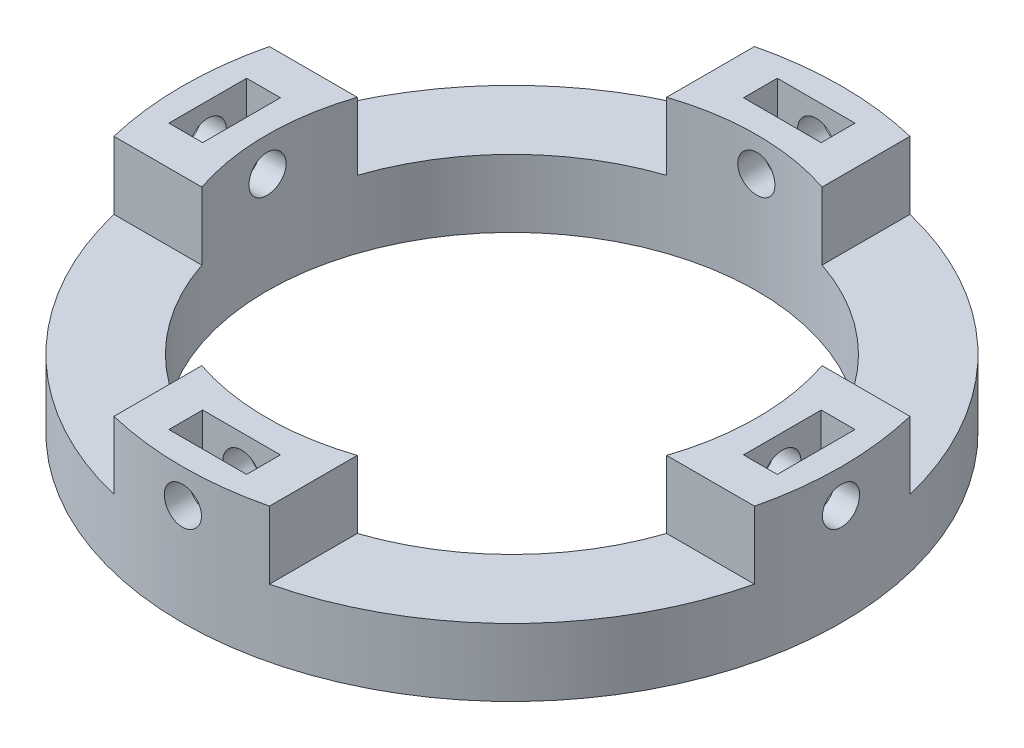
SolidWorks part; units mm, degrees
ref_plane "Спереди" through (0, 0, 0) normal (0, 0, 1) x (1, 0, 0)
ref_plane "Сверху" through (0, 0, 0) normal (0, 1, 0) x (1, 0, 0)
ref_plane "Справа" through (0, 0, 0) normal (1, 0, 0) x (0, 0, -1)
sketch "Эскиз1" plane through (0, 0, 0) normal (0, 1, 0) x (1, 0, 0)
  circle A0 centre (0, 0) radius 19.5
  circle A1 centre (0, 0) radius 14.5
  dimension "D1" = 29
  dimension "D2" = 39
extrude "Бобышка-Вытянуть1" add sketch "Эскиз1" along normal blind 4
sketch "Эскиз3" plane through (0, 4, 0) normal (0, 1, 0) x (1, 0, 0)
  line L0 (0, 24.1732) -> (0, -23.3198) construction
  line L2 (2.3, 18) -> (-2.3, 18)
  line L3 (2.3, 18) -> (2.3, 16)
  line L4 (2.3, 16) -> (-2.3, 16)
  line L5 (-2.3, 18) -> (-2.3, 16)
  line L6 (2.3, 18) -> (-2.3, 16) construction
  line L7 (2.3, 16) -> (-2.3, 18) construction
  line L18 (-4.6, 18.9497) -> (-4.6, 13.751)
  line L26 (4.6, 13.751) -> (4.6, 18.9497)
  line L27 (18, -2.3) -> (18, 2.3)
  line L28 (18, -2.3) -> (16, -2.3)
  line L29 (16, -2.3) -> (16, 2.3)
  line L30 (18, 2.3) -> (16, 2.3)
  line L31 (18.9497, 4.6) -> (13.751, 4.6)
  line L32 (13.751, -4.6) -> (18.9497, -4.6)
  line L33 (18, -2.3) -> (16, 2.3) construction
  line L34 (16, -2.3) -> (18, 2.3) construction
  line L35 (-2.3, -18) -> (2.3, -18)
  line L36 (-2.3, -18) -> (-2.3, -16)
  line L37 (-2.3, -16) -> (2.3, -16)
  line L38 (2.3, -18) -> (2.3, -16)
  line L39 (4.6, -18.9497) -> (4.6, -13.751)
  line L40 (-4.6, -13.751) -> (-4.6, -18.9497)
  line L41 (-2.3, -18) -> (2.3, -16) construction
  line L42 (-2.3, -16) -> (2.3, -18) construction
  line L43 (-18, 2.3) -> (-18, -2.3)
  line L44 (-18, 2.3) -> (-16, 2.3)
  line L45 (-16, 2.3) -> (-16, -2.3)
  line L46 (-18, -2.3) -> (-16, -2.3)
  line L47 (-18.9497, -4.6) -> (-13.751, -4.6)
  line L48 (-13.751, 4.6) -> (-18.9497, 4.6)
  line L49 (-18, 2.3) -> (-16, -2.3) construction
  line L50 (-16, 2.3) -> (-18, -2.3) construction
  circle A2 centre (0, 0) radius 17 construction
  arc A12 (4.6, 13.751) -> (-4.6, 13.751) centre (0, 0) ccw
  arc A13 (-13.751, 4.6) -> (-13.751, -4.6) centre (0, 0) ccw
  arc A14 (13.751, -4.6) -> (13.751, 4.6) centre (0, 0) ccw
  arc A15 (-4.6, -13.751) -> (4.6, -13.751) centre (0, 0) ccw
  arc A16 (-18.9497, 4.6) -> (-18.9497, -4.6) centre (0, 0) ccw
  arc A17 (4.6, 18.9497) -> (-4.6, 18.9497) centre (0, 0) ccw
  arc A18 (18.9497, -4.6) -> (18.9497, 4.6) centre (0, 0) ccw
  arc A19 (-4.6, -18.9497) -> (4.6, -18.9497) centre (0, 0) ccw
  point P5 (0, 17)
  point P12 (17, 0)
  point P13 (0, 22.5)
  point P14 (0, 19.5)
  point P28 (19.5, 0)
  point P32 (0, -17)
  point P38 (0, -19.5)
  point P42 (-17, 0)
  point P48 (-19.5, 0)
  point P52 (0, 0)
  dimension "D1" = 9.2
  dimension "D4" = 34
  dimension "D7" = 5.1987
  dimension "D8" = 4
  dimension "D2" = 2
  dimension "D3" = 4.6
extrude "Бобышка-Вытянуть3" add sketch "Эскиз3" along normal blind 4
sketch "Эскиз12" plane through (0, 0, -18) normal (0, 0, 1) x (1, 0, 0)
  line L0 (2.3, 8) -> (2.3, 4) construction
  line L1 (2.3, 8) -> (-2.3, 8) construction
  circle A0 centre (0, 6) radius 1.1
  dimension "D1" = 2.2
  dimension "D2" = 2.3
  dimension "D3" = 2
extrude "Вырез-Вытянуть2" cut sketch "Эскиз12" against normal through all both and the other way through all
pattern_circular "Круговой массив2" count 2 every 90 about axis through (0, 4, 0) along (0, -1, 0) of "Вырез-Вытянуть2"
